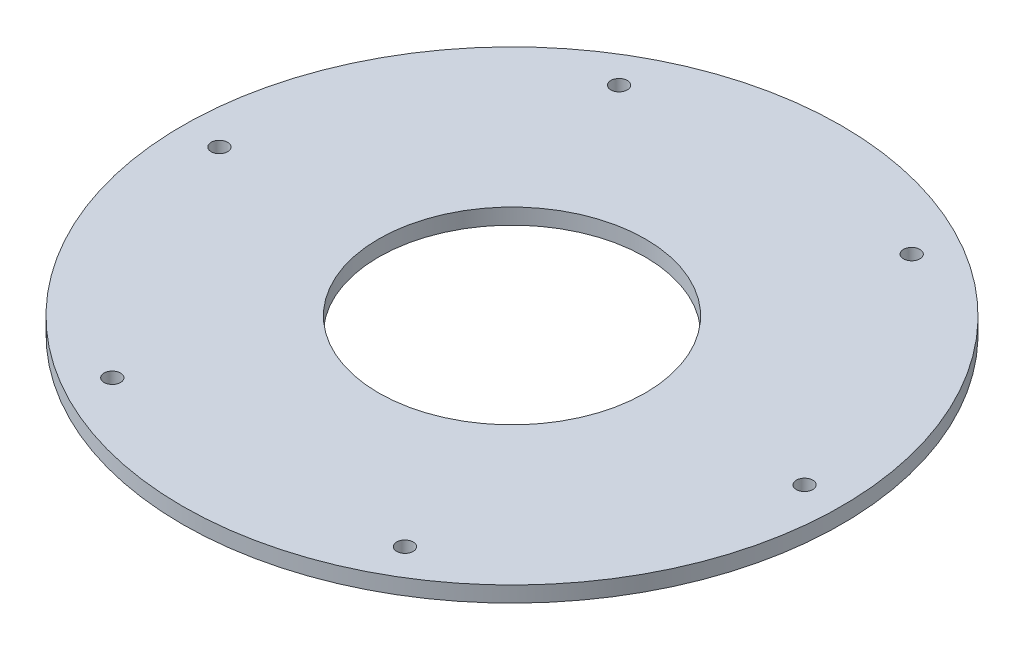
SolidWorks part; units mm, degrees
material "1060 Alloy"
ref_plane "Front Plane" through (0, 0, 0) normal (0, 0, 1) x (1, 0, 0)
ref_plane "Top Plane" through (0, 0, 0) normal (0, 1, 0) x (1, 0, 0)
ref_plane "Right Plane" through (0, 0, 0) normal (1, 0, 0) x (0, 0, -1)
sketch "Sketch2" plane through (0, 0, 0) normal (0, 1, 0) x (1, 0, 0)
  line L0 (-37.2875, 0) -> (0, 0) construction
  circle A0 centre (0, 0) radius 42
  circle A1 centre (0, 0) radius 37.2875 construction
  circle A2 centre (-37.2875, 0) radius 1.05
  circle A3 centre (-18.6438, 32.2919) radius 1.05
  circle A4 centre (18.6438, 32.2919) radius 1.05
  circle A5 centre (37.2875, 0) radius 1.05
  circle A6 centre (18.6438, -32.2919) radius 1.05
  circle A7 centre (-18.6437, -32.2919) radius 1.05
  circle A8 centre (0, 0) radius 17
  point P6 (0, 0)
  point P18 (0, 0)
  dimension "D1" = 2.1
  dimension "D3" = 74.575
  dimension "D4" = 84
  dimension "D5" = 34
  dimension "D2" = 6
extrude "Boss-Extrude1" add sketch "Sketch2" along normal blind 2
equation "\"D5@Sketch2\" = \"Rotor_ID\""
equation "\"Stator_OD\"= 68'No Tolerance given"
equation "\"A\"=18.34"
equation "\"Rotor_ID\"= 34'No Tolerance Given"
equation "\"back_bearing_Thickness\"= 20'Currently non-sense"
equation "\"back_bearing_OD\"= 60'currently non-sense"
equation "\"Stator_Gap\"= 0.0375'+- 0.0125 (From 1.3.3.1 Kollmorgen manual)"
equation "\"Back_mount_hole\"= 1.75'To be tapped to M2 (USE LOCKTITE)"
equation "\"facePlate_Mount_Hole\"= 5.75'To be tapped to M6"
equation "\"back_bearing_ID\"= 40'Random number"
equation "\"final_shaftD\"= 8'NEMA 23 shaft diameter. Should fit with harmonic?"
equation "\"final_shaftL\"= 50'random length. Idk"
equation "\"back_bearing_IDOD\"= 45'Random number, OD of the inner bearing ring"
equation "\"rotor_shaftD\"= \"Rotor_ID\" - (0.0185)*2'+-0.0065 (from manual)"
equation "\"D4@Sketch2\"=\"Stator_OD\"+16"
equation "\"D3@Sketch2\"=\"Stator_OD\"+\"Stator_Gap\"*2+6.5"
